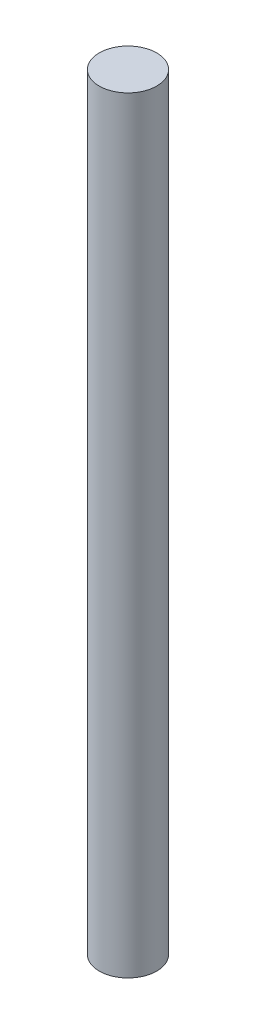
SolidWorks part; units mm, degrees
ref_plane "Front Plane" through (0, 0, 0) normal (0, 0, 1) x (1, 0, 0)
ref_plane "Top Plane" through (0, 0, 0) normal (0, 1, 0) x (1, 0, 0)
ref_plane "Right Plane" through (0, 0, 0) normal (1, 0, 0) x (0, 0, -1)
sketch "Sketch2" plane through (0, 0, 0) normal (0, 1, 0) x (1, 0, 0)
  line L0 (-289.0087, -6.3326) -> (-289.0087, -156.3326) construction
  line L1 (-214.0087, -81.3326) -> (-364.0087, -81.3326) construction
  circle A0 centre (-289.0087, -81.3326) radius 75
extrude "Boss-Extrude1" add sketch "Sketch2" along normal blind 2000
sketch "Sketch3" plane through (0, 2000, 0) normal (0, 1, 0) x (1, 0, 0)
  line L0 (-214.0087, -81.3326) -> (-364.0087, -81.3326) construction
  line L1 (-289.0087, -6.3326) -> (-289.0087, -156.3326) construction
  line L2 (-214.0087, -81.3326) -> (-364.0087, -81.3326) construction
  line L3 (-289.0087, -6.3326) -> (-289.0087, -156.3326) construction
  circle A1 centre (-289.0087, -81.3326) radius 75
  circle A2 centre (-289.0087, -81.3326) radius 75 construction
  dimension "D1" = 0
sketch3d "3DSketch1"
  line L0 (-289.0087, 2000, 156.3326) -> (-289.0087, 0, 156.3326) construction
sketch3d "3DSketch2"
  line L0 (-289.0087, 0, 6.3326) -> (-289.0087, 2000, 6.3326) construction
  line L1 (-289.0087, 0, 6.3326) -> (-289.0087, 0, 156.3326) construction
  line L2 (-289.0087, 2000, 6.3326) -> (-289.0087, 2000, 156.3326) construction
  circle A0 centre (-289.0087, 2000, 81.3326) radius 75 construction
  point P8 (-289.0087, 2075, 81.3326)
